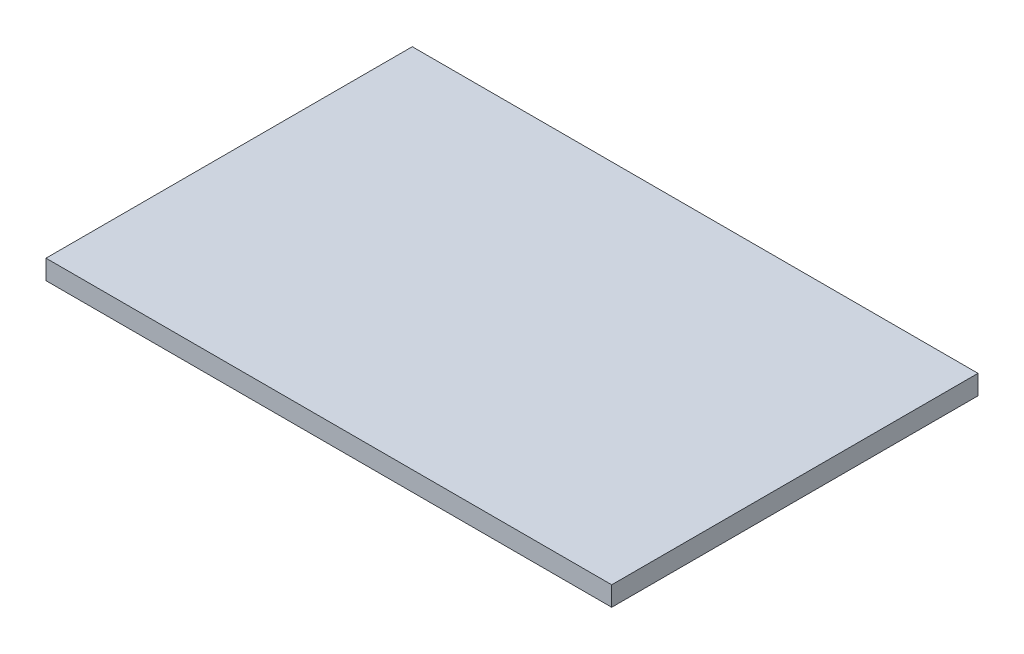
SolidWorks part; units mm, degrees
ref_plane "Front Plane" through (0, 0, 0) normal (0, 0, 1) x (1, 0, 0)
ref_plane "Top Plane" through (0, 0, 0) normal (0, 1, 0) x (1, 0, 0)
ref_plane "Right Plane" through (0, 0, 0) normal (1, 0, 0) x (0, 0, -1)
sketch "Sketch1" plane through (0, 0, 0) normal (0, 1, 0) x (1, 0, 0)
  line L0 (-21.02, 11.515) -> (-21.02, -15.705)
  line L1 (21.02, -11.515) -> (-21.02, -11.515) construction
  line L2 (21.02, -11.515) -> (21.02, 11.515) construction
  line L3 (21.02, 11.515) -> (-21.02, 11.515)
  line L4 (-21.02, -11.515) -> (-21.02, 11.515) construction
  line L5 (21.02, -11.515) -> (-21.02, 11.515) construction
  line L6 (21.02, 11.515) -> (-21.02, -11.515) construction
  line L7 (-21.02, -15.705) -> (21.02, -15.705)
  line L8 (21.02, -15.705) -> (21.02, 11.515)
  line L10 (17.526, -8.758) -> (-17.526, -8.758) construction
  line L11 (17.526, -8.758) -> (17.526, 8.758) construction
  line L12 (17.526, 8.758) -> (-17.526, 8.758) construction
  line L13 (-17.526, -8.758) -> (-17.526, 8.758) construction
  line L14 (17.526, -8.758) -> (-17.526, 8.758) construction
  line L15 (17.526, 8.758) -> (-17.526, -8.758) construction
  point P0 (0, 0)
  point P8 (0, 0)
  dimension "D1" = 42.04
  dimension "D2" = 23.03
  dimension "D3" = 27.22
  dimension "D4" = 35.052
  dimension "D5" = 17.516
extrude "Boss-Extrude1" add sketch "Sketch1" along normal blind 1.45
